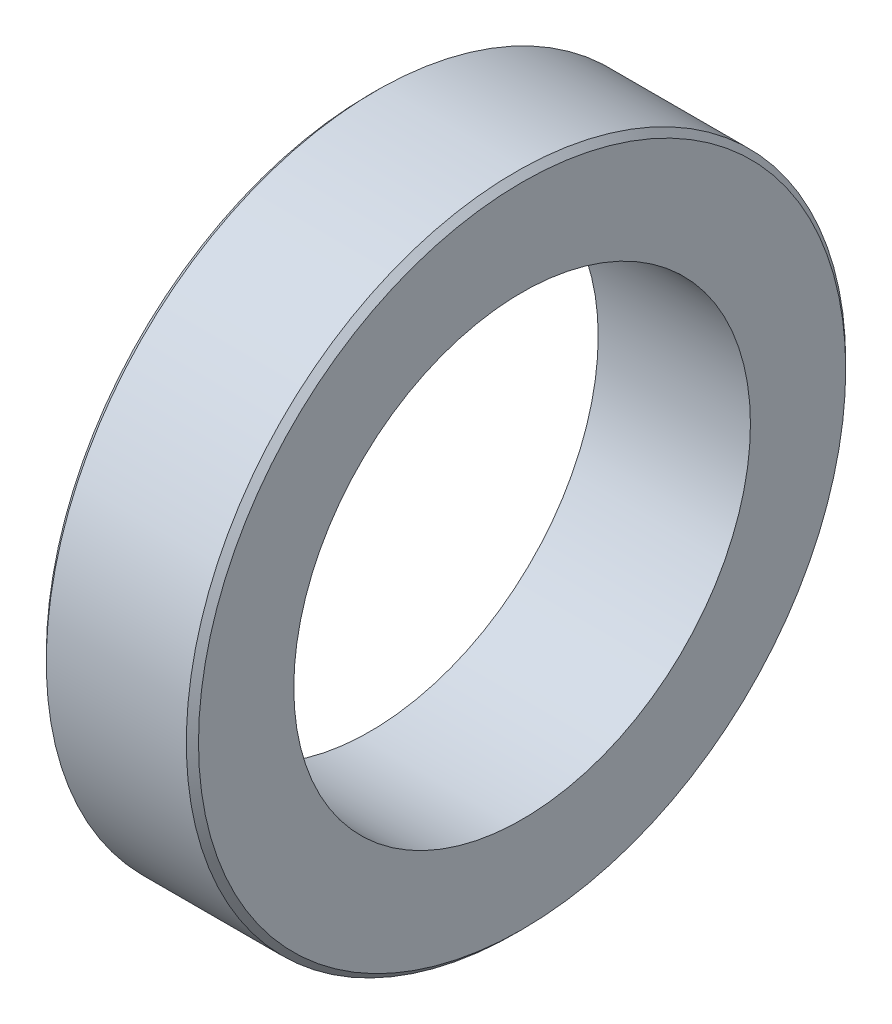
SolidWorks part; units mm, degrees
ref_plane "Front Plane" through (0, 0, 0) normal (1, 0, 0) x (0, 1, 0)
ref_plane "Top Plane" through (0, 0, 0) normal (0, 0, 1) x (0, 1, 0)
ref_plane "Right Plane" through (0, 0, 0) normal (0, 1, 0) x (-1, 0, 0)
sketch "Sketch1" plane through (0, 0, 0) normal (1, 0, 0) x (0, 1, 0)
  circle A0 centre (0, 0) radius 82.5246
extrude "Boss-Extrude1" add sketch "Sketch1" along normal blind 38.1
sketch "Sketch2" plane through (0, 0, 0) normal (1, 0, 0) x (0, 1, 0)
  circle A0 centre (0, 0) radius 57.15
extrude "Cut-Extrude1" cut sketch "Sketch2" along normal blind 38.1
chamfer "Chamfer1" distance 1.524 angle 45 2 edges at (38.1, 0, -82.5246) (0, 0, -82.5246)
